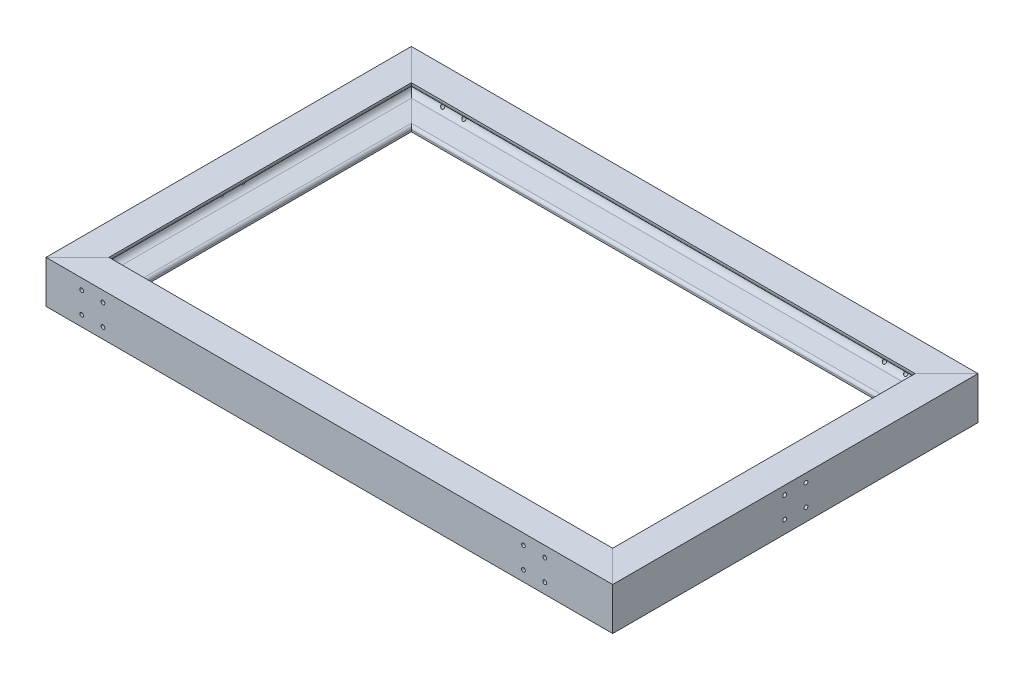
SolidWorks part; units mm, degrees
ref_plane "前视基准面" through (0, 0, 0) normal (0, 0, 1) x (1, 0, 0)
ref_plane "上视基准面" through (0, 0, 0) normal (0, 1, 0) x (1, 0, 0)
ref_plane "右视基准面" through (0, 0, 0) normal (1, 0, 0) x (0, 0, -1)
sketch "草图1" plane through (0, 0, 0) normal (0, 1, 0) x (1, 0, 0)
  line L1 (-333.5, 215) -> (333.5, 215)
  line L2 (-333.5, 215) -> (-333.5, -215)
  line L3 (-333.5, -215) -> (333.5, -215)
  line L4 (333.5, 215) -> (333.5, -215)
  line L5 (-333.5, 215) -> (333.5, -215) construction
  line L6 (-333.5, -215) -> (333.5, 215) construction
  point P0 (0, 0)
  dimension "D1" = 430
  dimension "D2" = 667
other "热轧槽钢gb∕t706-2008 5(1)"
ref_plane "基准面1" through (-333.5, 0, -215) normal (-1, 0, 0) x (0, 0, 1)
sketch "Sketch17" plane through (-333.5, 0, -215) normal (-1, 0, 0) x (0, 0, 1)
  line L0 (37, 50) -> (0, 50)
  line L1 (37, 0) -> (0, 0)
  line L2 (0, 50) -> (0, 0)
  line L3 (-9.5694, 25) -> (49.7414, 25) construction
  line L4 (4.5, 34.9892) -> (4.5, 15.0108)
  line L5 (37, 0) -> (37, 2.1406)
  line L6 (37, 50) -> (37, 47.8594)
  line L7 (10.7683, 8.0491) -> (33.8658, 5.6215)
  line L17 (10.7683, 41.9509) -> (33.8658, 44.3785)
  arc A0 (33.8658, 44.3785) -> (37, 47.8594) centre (33.5, 47.8594) ccw
  arc A1 (33.8658, 5.6215) -> (37, 2.1406) centre (33.5, 2.1406) cw
  arc A2 (4.5, 15.0108) -> (10.7683, 8.0491) centre (11.5, 15.0108) ccw
  arc A10 (4.5, 34.9892) -> (10.7683, 41.9509) centre (11.5, 34.9892) cw
  point P6 (0, 0)
  point P8 (0, 25)
  point P9 (4.5, 25.8841)
  point P10 (18.5, 50)
  point P13 (37, 44.7079)
  point P14 (20.75, 43)
  point P19 (4.5, 25)
  dimension "D4" = 3.5
  dimension "D5" = 25
  dimension "RI" = 7
  dimension "D2" = 6
  dimension "D1" = 7
  dimension "D3" = 16.25
  dimension "D6" = 4.5
  dimension "Depth" = 50
  dimension "BF" = 37
sketch "草图10" plane through (0, 0, 0) normal (0, 0, 1) x (1, 0, 0)
  line L0 (0, 0) -> (0, 232.8908) construction
  line L1 (241, 50) -> (241, 0) construction
  line L2 (253.5, 12.5) -> (228.5, 12.5)
  line L3 (253.5, 12.5) -> (253.5, 37.5)
  line L4 (253.5, 37.5) -> (228.5, 37.5)
  line L5 (228.5, 12.5) -> (228.5, 37.5)
  line L6 (253.5, 12.5) -> (228.5, 37.5) construction
  line L7 (253.5, 37.5) -> (228.5, 12.5) construction
  line L9 (-333.5, 50) -> (333.5, 50) construction
  line L10 (-333.5, 0) -> (333.5, 0) construction
  line L11 (333.5, 50) -> (333.5, 0) construction
  circle A0 centre (228.5, 37.5) radius 2.25
  circle A1 centre (253.5, 37.5) radius 2.25
  circle A2 centre (253.5, 12.5) radius 2.25
  circle A3 centre (228.5, 12.5) radius 2.25
  point P3 (241, 25)
  dimension "D3" = 4.5
  dimension "D1" = 25
  dimension "D2" = 80
extrude "切除-拉伸1" cut sketch "草图10" against normal through all both and the other way through all contours L4 A1 L3 | L5 A0 L4 | L3 A2 L2 | L2 A3 L5 | L5 A3 L2 | L2 A2 L3 | L3 A1 L4 | L4 A0 L5
pattern_linear "阵列(线性)1" count 2 spacing 520 along (-1, 0, 0) of "切除-拉伸1"
sketch "草图11" plane through (333.5, 0, 0) normal (1, 0, 0) x (0, 0, -1)
  line L0 (-215, 0) -> (215, 0) construction
  line L1 (-12.5, 40) -> (12.5, 40)
  line L2 (-12.5, 40) -> (-12.5, 15)
  line L3 (-12.5, 15) -> (12.5, 15)
  line L4 (12.5, 40) -> (12.5, 15)
  line L5 (-12.5, 40) -> (12.5, 15) construction
  line L6 (-12.5, 15) -> (12.5, 40) construction
  line L7 (0, 27.5) -> (0, 0) construction
  circle A0 centre (-12.5, 40) radius 2.25
  circle A1 centre (12.5, 40) radius 2.25
  circle A2 centre (12.5, 15) radius 2.25
  circle A3 centre (-12.5, 15) radius 2.25
  point P0 (0, 27.5)
  dimension "D3" = 4.5
  dimension "D1" = 25
  dimension "D2" = 15
extrude "切除-拉伸2" cut sketch "草图11" against normal through all both and the other way through all contours L2 A0 L1 | L3 A3 L2 | L4 A2 L3 | L1 A1 L4 | L4 A1 L1 | L1 A0 L2 | L2 A3 L3 | L3 A2 L4
